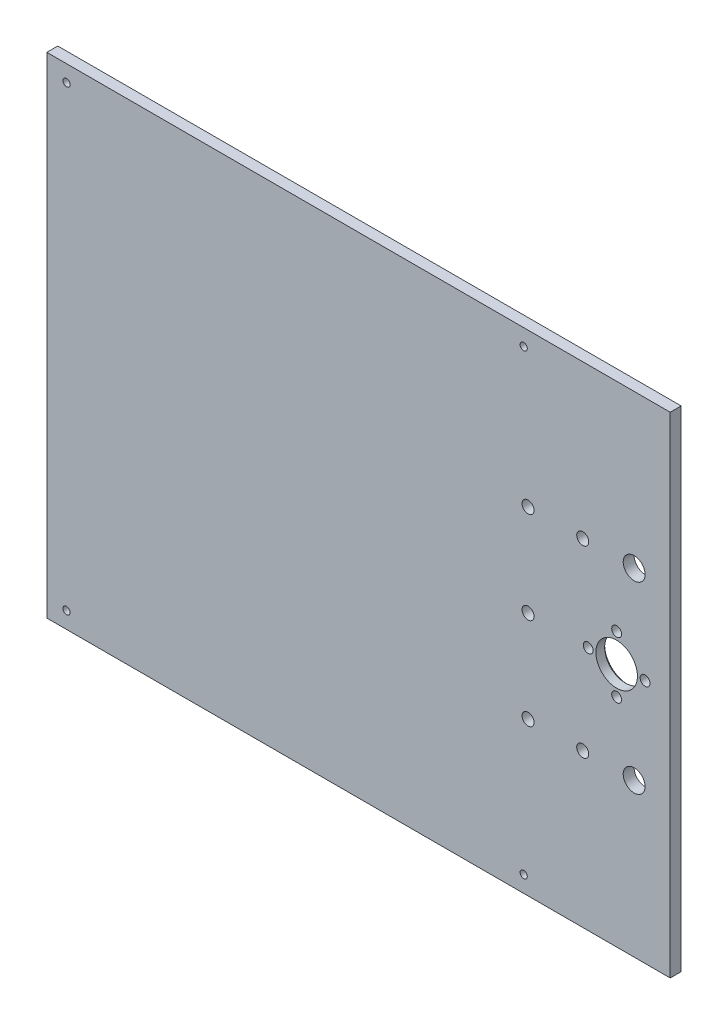
SolidWorks part; units mm, degrees
material "Lega 1060"
ref_plane "Piano frontale" through (0, 0, 0) normal (0, 0, 1) x (1, 0, 0)
ref_plane "Piano superiore" through (0, 0, 0) normal (0, 1, 0) x (1, 0, 0)
ref_plane "Piano destro" through (0, 0, 0) normal (1, 0, 0) x (0, 0, -1)
sketch "Schizzo1" plane through (0, 0, 0) normal (0, 0, 1) x (1, 0, 0)
  line L1 (0, 20) -> (-285, 20)
  line L2 (0, 20) -> (0, 244)
  line L3 (0, 244) -> (-285, 244)
  line L4 (-285, 20) -> (-285, 244)
  dimension "D1" = 285
  dimension "D2" = 224
  dimension "D3" = 20
extrude "Estrusione-Estrusione1" add sketch "Schizzo1" along normal blind 5
sketch "Schizzo2" plane through (0, 0, 0) normal (0, 0, -1) x (-1, 0, 0)
  circle A0 centre (24.5, 132) radius 9.5
  dimension "D1" = 19
extrude "Taglio-Estrusione1" cut sketch "Schizzo2" against normal up to next
chamfer "Smusso1" distance 1 angle 45 1 edges at (-34, 132, 0)
hole_wizard "Foro per Vite M4-1" positions "Schizzo4" profile "Schizzo3" hole size "M4" standard "ISO"
sketch "Schizzo4" plane through (0, 0, 0) normal (0, 0, -1) x (-1, 0, 0)
  line L0 (24.5, 145) -> (24.5, 119) construction
  point P0 (24.5, 119)
  point P3 (37.5, 132)
  point P6 (24.5, 145)
  point P9 (11.5, 132)
sketch "Schizzo3" plane through (-24.5, 119, 0) normal (1, 0, 0) x (0, 1, 0)
  line L0 (0, 0) -> (0, 9.3519)
  line L1 (0, 9.3519) -> (2.25, 8)
  line L2 (2.25, 8) -> (2.25, 0)
  line L5 (2.25, 0) -> (0, 0)
  line L10 (0, 9.3519) -> (-2.25, 8) construction
  line L11 (0, -6.35) -> (0, 107.95) construction
  dimension "Hole Dia." = 4.5
  dimension "Hole Depth" = 8
  dimension "Drill Angle" = 118
sketch "Schizzo6" plane through (0, 0, 5) normal (0, 0, 1) x (1, 0, 0)
  circle A0 centre (-16.5, 90) radius 5
  circle A1 centre (-16.5, 174) radius 5
  dimension "D1" = 10
  dimension "D2" = 10
extrude "Taglio-Estrusione2" cut sketch "Schizzo6" against normal up to next
hole_wizard "Foro per Vite M5-2" positions "Schizzo8" profile "Schizzo7" hole size "M5" standard "ISO" end condition up to next
sketch "Schizzo8" plane through (0, 0, 5) normal (0, 0, 1) x (1, 0, 0)
  line L2 (0, 244) -> (-285, 244) construction
  line L3 (0, 20) -> (0, 244) construction
  line L4 (-89.6625, 132) -> (-52.1719, 132) construction
  point P0 (-27.953, 298.6689)
  point P1 (-40, 90)
  point P3 (-65, 132)
  point P5 (-40, 174)
  point P27 (-65, 174)
  point P29 (-65, 90)
  dimension "D1" = 25
  dimension "D2" = 42
  dimension "D3" = 42
  dimension "D4" = 112
  dimension "D5" = 65
  dimension "D6" = 42
  dimension "D7" = 65
sketch "Schizzo7" plane through (-27.953, 298.6689, 5) normal (1, 0, 0) x (0, -1, 0)
  line L0 (0, 0) -> (0, 5)
  line L1 (0, 5) -> (2.75, 5)
  line L2 (2.75, 5) -> (2.75, 0)
  line L5 (2.75, 0) -> (0, 0)
  line L11 (0, -6.35) -> (0, 107.95) construction
  dimension "Thru Hole Dia." = 5.5
  dimension "Thru Hole Depth" = 5
hole_wizard "Foro filettato M4-1" positions "Schizzo11" profile "Schizzo10" tap size "M4" standard "ISO" end condition up to next
sketch "Schizzo11" plane through (0, 0, 0) normal (0, 0, -1) x (-1, 0, 0)
  line L0 (285, 20) -> (0, 20) construction
  point P0 (276, 27.5)
  point P2 (67, 27.5)
  point P4 (276, 236.5)
  point P6 (67, 236.5)
  dimension "D1" = 7.5
  dimension "D2" = 209
  dimension "D3" = 209
  dimension "D4" = 9
sketch "Schizzo10" plane through (-276, 27.5, 0) normal (1, 0, 0) x (0, 1, 0)
  line L0 (0, 0) -> (0, 5)
  line L1 (0, 5) -> (1.65, 5)
  line L2 (1.65, 5) -> (1.65, 0)
  line L5 (1.65, 0) -> (0, 0)
  line L11 (0, -6.35) -> (0, 107.95) construction
  dimension "Thru Tap Drill Dia." = 3.3
  dimension "Thru Tap Drill Depth" = 5
cosmetic thread "Filettatura del foro1" parameters "D2"=4
cosmetic thread "Filettatura del foro2" parameters "D2"=4
cosmetic thread "Filettatura del foro3" parameters "D2"=4
cosmetic thread "Filettatura del foro4" parameters "D2"=4
